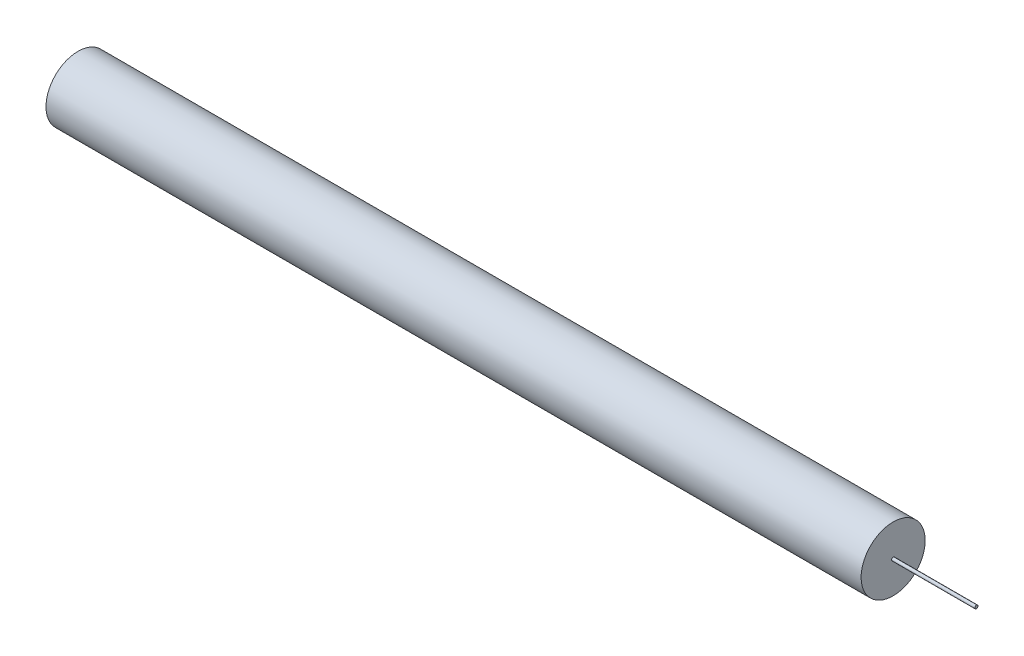
SolidWorks part; units mm, degrees
ref_plane "Front Plane" through (0, 0, 0) normal (0, 0, 1) x (1, 0, 0)
ref_plane "Top Plane" through (0, 0, 0) normal (0, 1, 0) x (1, 0, 0)
ref_plane "Right Plane" through (0, 0, 0) normal (1, 0, 0) x (0, 0, -1)
sketch "Sketch1" plane through (0, 0, 0) normal (0, 0, 1) x (1, 0, 0)
  line L0 (0, 0) -> (509.0859, 0)
  line L1 (0, 0) -> (561.0859, 0) construction
  point P9 (561.0859, 0)
  dimension "D1" = 52
sketch "Sketch2" plane through (0, 0, 0) normal (1, 0, 0) x (0, 0, -1)
  circle A0 centre (0, 0) radius 20
  dimension "D1" = 40
sweep "Sweep1" add path "Sketch1" circular profile diameter 40 parameters "D3"=40
sketch "Sketch16" plane through (0, 0, 0) normal (0, 0, 1) x (1, 0, 0)
  line L0 (509.0859, -20) -> (509.0859, 20) construction
  line L1 (509.0859, -20) -> (509.0859, 20) construction
  line L2 (561.0859, 0) -> (509.0859, 0)
  point P2 (561.0859, 0)
sweep "Sweep2" add path "Sketch16" circular profile diameter 2 parameters "D3"=2
